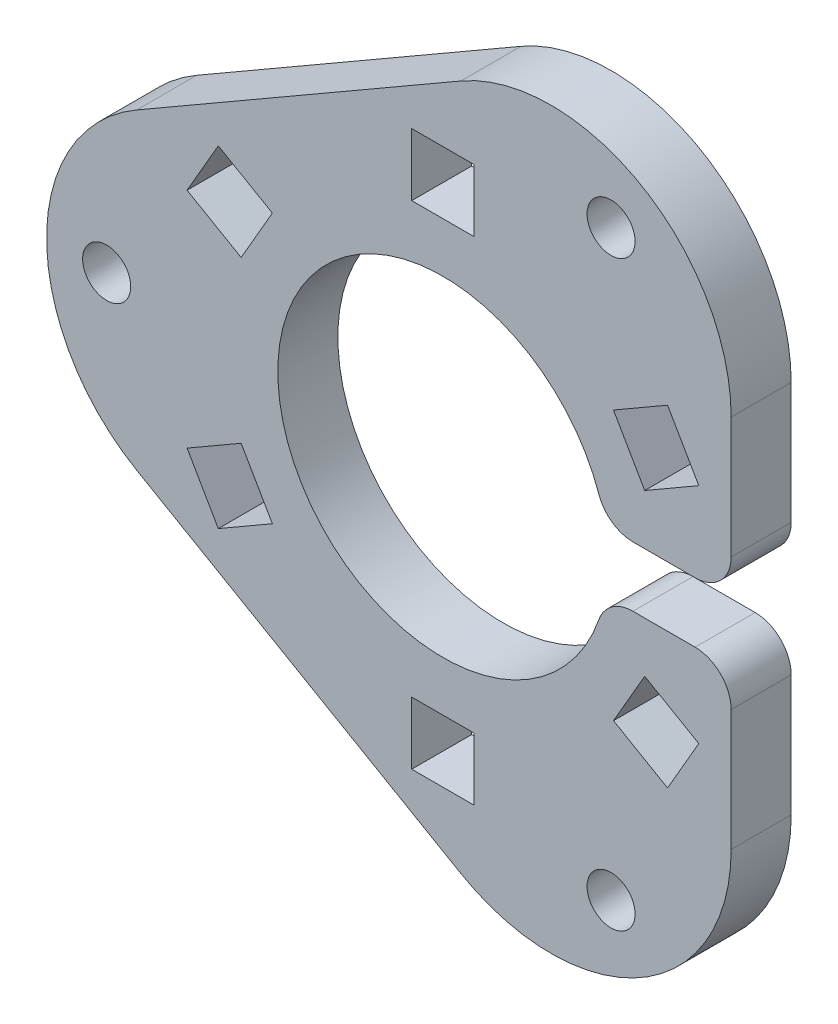
SolidWorks part; units mm, degrees
ref_plane "Front Plane" through (0, 0, 0) normal (0, 0, 1) x (1, 0, 0)
ref_plane "Top Plane" through (0, 0, 0) normal (0, 1, 0) x (1, 0, 0)
ref_plane "Right Plane" through (0, 0, 0) normal (1, 0, 0) x (0, 0, -1)
sketch "Sketch1" plane through (0, 0, 0) normal (0, 0, 1) x (1, 0, 0)
  line L0 (-26, 0) -> (26, 0) construction
  line L7 (-2.6, 23.1) -> (2.6, 23.1)
  line L8 (-2.6, 23.1) -> (-2.6, 17.9)
  line L9 (-2.6, 17.9) -> (2.6, 17.9)
  line L10 (2.6, 23.1) -> (2.6, 17.9)
  line L23 (0, 26) -> (0, -26) construction
  line L24 (21.3052, 9.2983) -> (16.8019, 6.6983)
  line L25 (14.2019, 11.2017) -> (16.8019, 6.6983)
  line L26 (18.7052, 13.8017) -> (14.2019, 11.2017)
  line L27 (18.7052, 13.8017) -> (21.3052, 9.2983)
  line L28 (18.7052, -13.8017) -> (14.2019, -11.2017)
  line L29 (16.8019, -6.6983) -> (14.2019, -11.2017)
  line L30 (21.3052, -9.2983) -> (16.8019, -6.6983)
  line L31 (21.3052, -9.2983) -> (18.7052, -13.8017)
  line L32 (-2.6, -23.1) -> (-2.6, -17.9)
  line L33 (2.6, -17.9) -> (-2.6, -17.9)
  line L34 (2.6, -23.1) -> (2.6, -17.9)
  line L35 (2.6, -23.1) -> (-2.6, -23.1)
  line L36 (-21.3052, -9.2983) -> (-16.8019, -6.6983)
  line L37 (-14.2019, -11.2017) -> (-16.8019, -6.6983)
  line L38 (-18.7052, -13.8017) -> (-14.2019, -11.2017)
  line L39 (-18.7052, -13.8017) -> (-21.3052, -9.2983)
  line L40 (-18.7052, 13.8017) -> (-14.2019, 11.2017)
  line L41 (-16.8019, 6.6983) -> (-14.2019, 11.2017)
  line L42 (-21.3052, 9.2983) -> (-16.8019, 6.6983)
  line L43 (-21.3052, 9.2983) -> (-18.7052, 13.8017)
  line L44 (24, 2.5) -> (13.5208, 2.5)
  line L45 (24, -2.5) -> (13.5208, -2.5)
  line L46 (24, 41.5692) -> (24, -41.5692) construction
  line L47 (24, -41.5692) -> (-48, 0) construction
  line L48 (-48, 0) -> (24, 41.5692) construction
  line L49 (24, 2.5) -> (24, 41.5692)
  line L50 (24, 41.5692) -> (-48, 0)
  line L51 (-48, 0) -> (24, -41.5692)
  line L52 (24, -41.5692) -> (24, -2.5)
  line L53 (0, 0) -> (24, 41.5692) construction
  line L54 (-2.6, 20.5) -> (2.6, 20.5) construction
  circle A0 centre (0, 0) radius 13.75 construction
  arc A2 (13.5208, 2.5) -> (13.5208, -2.5) centre (0, 0) ccw
  circle A4 centre (14, 24.2487) radius 2
  circle A5 centre (14, -24.2487) radius 2
  circle A6 centre (-28, 0) radius 2
  point P40 (0, 0)
  point P48 (0, 0)
  point P50 (0, 0)
  dimension "D2" = 24
  dimension "D1" = 27.5
  dimension "D10" = 4
  dimension "D3" = 5.2
  dimension "D4" = 5.2
  dimension "D5" = 20.5
  dimension "D6" = 6
  dimension "D7" = 5
  dimension "D9" = 28
  dimension "D11" = 3
  dimension "D8" = 3
extrude "Boss-Extrude1" add sketch "Sketch1" along normal blind 5
fillet "Congé1" radius 15 3 edges at (24, -41.5692, 2.5) (-48, 0, 2.5) (24, 41.5692, 2.5)
fillet "Congé2" radius 3 4 edges at (13.5208, 2.5, 2.5) (13.5208, -2.5, 2.5) (24, -2.5, 2.5) (24, 2.5, 2.5)
